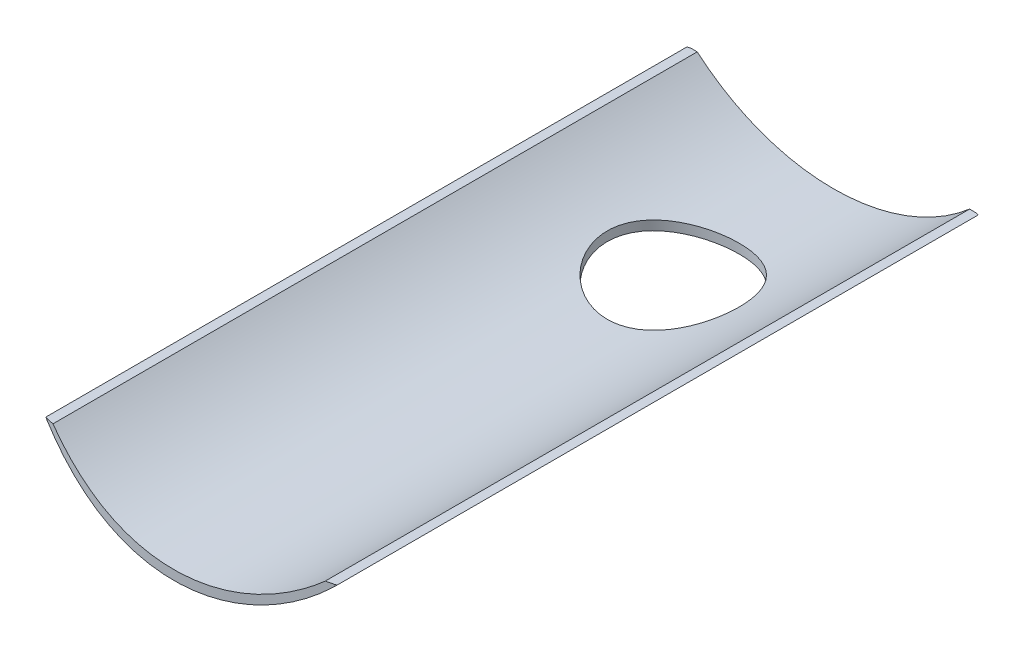
SolidWorks part; units mm, degrees
material "Silicon Rubber"
ref_plane "Front Plane" through (0, 0, 0) normal (0, 0, 1) x (1, 0, 0)
ref_plane "Top Plane" through (0, 0, 0) normal (0, 1, 0) x (1, 0, 0)
ref_plane "Right Plane" through (0, 0, 0) normal (1, 0, 0) x (0, 0, -1)
sketch "Sketch1" plane through (0, 0, 0) normal (0, 1, 0) x (1, 0, 0)
  line L2 (8, -16.5) -> (8, 17.5)
  line L3 (8, 17.5) -> (-8, 17.5)
  line L4 (-8, -16.5) -> (-8, 17.5)
  line L5 (7.5892, -16.6015) -> (-8, 17.5) construction
  line L6 (8, 17.5) -> (-7.5892, -16.6015) construction
  arc A0 (-8, -16.5) -> (8, -16.5) centre (0, 15) ccw
  point P1 (0, 0)
  dimension "D2" = 16
extrude "Boss-Extrude1" add sketch "Sketch1" along normal blind 8
fillet "Fillet1" radius 0.5 4 edges at (-8, 4, 16.5) (8, 4, 16.5) (8, 4, -17.5) (-8, 4, -17.5)
sketch "Sketch2" plane through (0, 8, 0) normal (0, 1, 0) x (1, 0, 0)
  line L0 (0, 17.5) -> (0, 9)
  line L1 (7.5, 17.5) -> (-7.5, 17.5) construction
  circle A0 centre (0, 9) radius 3.5
  dimension "D2" = 7
  dimension "D1" = 8.5
extrude "Cut-Extrude1" cut sketch "Sketch2" against normal blind 22.5
sketch "Sketch5" plane through (0, 0, -17.5) normal (0, 0, -1) x (-1, 0, 0)
  line L0 (-7.5, 8) -> (7.5, 8) construction
  line L1 (0, 8) -> (-7.725, 8)
  line L2 (0, 8) -> (7.725, 8)
  arc A0 (-7.725, 8) -> (7.725, 8) centre (0, 15.7243) ccw
  point P0 (0, 8)
  point P7 (0, 4.8)
  point P9 (0, 4.8)
  dimension "D1" = 7.725
  dimension "D2" = 7.725
  dimension "D3" = 3.2
extrude "Cut-Extrude2" cut sketch "Sketch5" against normal mid plane 79 flip side to cut
sketch "Sketch6" plane through (0, 0, -17.5) normal (0, 0, -1) x (-1, 0, 0)
  line L0 (-7.725, 8) -> (-7.225, 8)
  line L2 (7.725, 8) -> (7.225, 8)
  line L3 (-7.5, 8) -> (7.5, 8) construction
  arc A0 (7.725, 8) -> (-7.725, 8) centre (0, 15.796) cw
  arc A2 (-7.225, 8) -> (7.225, 8) centre (0, 16.4026) ccw
  point P10 (0, 5.3209)
  point P11 (0, 4.8209)
  dimension "D1" = 0.5
  dimension "D2" = 0.5
  dimension "D3" = 0.5
extrude "Cut-Extrude3" cut sketch "Sketch6" against normal mid plane 79 flip side to cut
